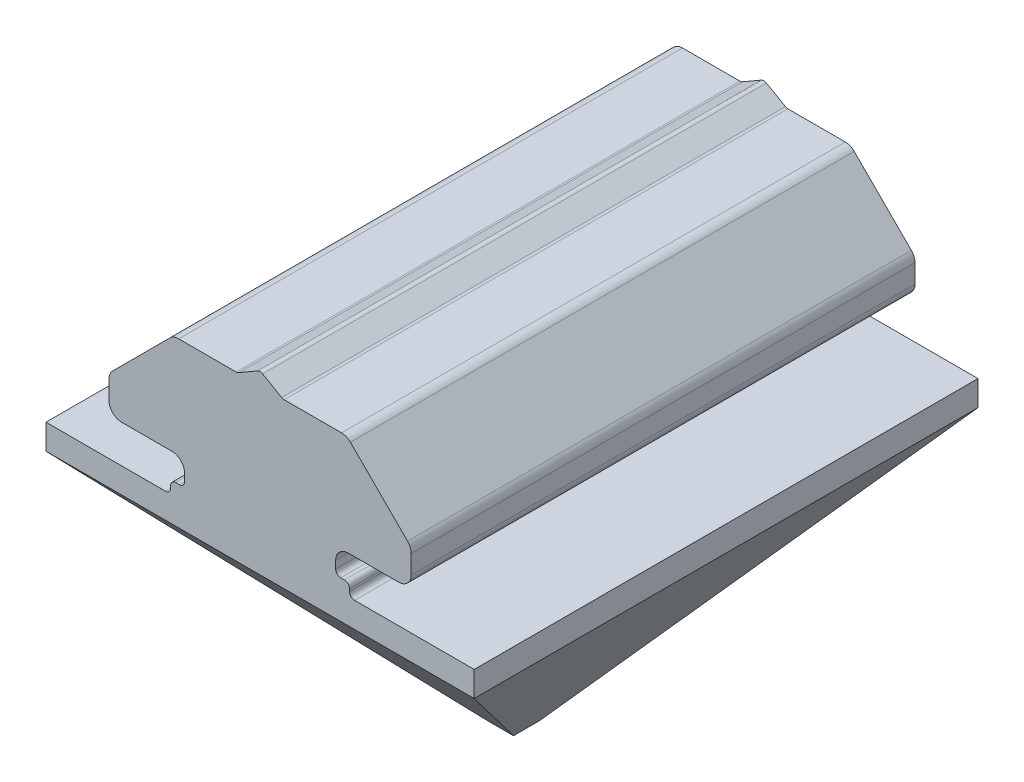
SolidWorks part; units mm, degrees
ref_plane "Front Plane" through (0, 0, 0) normal (0, 0, 1) x (1, 0, 0)
ref_plane "Top Plane" through (0, 0, 0) normal (0, 1, 0) x (1, 0, 0)
ref_plane "Right Plane" through (0, 0, 0) normal (1, 0, 0) x (0, 0, -1)
sketch "Sketch3" plane through (0, 0, 0) normal (0, 0, 1) x (1, 0, 0)
  line L44 (3.75, -10) -> (8.5, -10)
  line L45 (3.55, -9.7) -> (3.55, -9.8)
  line L46 (3.2, -9.5) -> (3.35, -9.5)
  line L47 (3, -9) -> (3, -9.3)
  line L48 (5.5, -8.5) -> (3.5, -8.5)
  line L49 (6, -7.2678) -> (6, -8)
  line L50 (3.5858, -4.6464) -> (5.8536, -6.9142)
  line L51 (0.9536, -4.5) -> (3.2322, -4.5)
  line L52 (0.1, -4.0381) -> (0.8536, -4.4732)
  line L53 (-0.8536, -4.4732) -> (-0.1, -4.0381)
  line L54 (-3.2322, -4.5) -> (-0.9536, -4.5)
  line L55 (-5.8536, -6.9142) -> (-3.5858, -4.6464)
  line L56 (-6, -8) -> (-6, -7.2678)
  line L57 (-3.5, -8.5) -> (-5.5, -8.5)
  line L58 (-3, -9.3) -> (-3, -9)
  line L59 (-3.35, -9.5) -> (-3.2, -9.5)
  line L60 (-3.55, -9.8) -> (-3.55, -9.7)
  line L61 (-8.5, -10) -> (-3.75, -10)
  line L62 (-8.5, -10) -> (-8.5, -11)
  line L63 (-8.5, -11) -> (8.5, -11)
  line L64 (8.5, -11) -> (8.5, -10)
  arc A44 (3.55, -9.8) -> (3.75, -10) centre (3.75, -9.8) ccw
  arc A45 (3.55, -9.7) -> (3.35, -9.5) centre (3.35, -9.7) ccw
  arc A46 (3, -9.3) -> (3.2, -9.5) centre (3.2, -9.3) ccw
  arc A47 (3.5, -8.5) -> (3, -9) centre (3.5, -9) ccw
  arc A48 (5.5, -8.5) -> (6, -8) centre (5.5, -8) ccw
  arc A49 (6, -7.2678) -> (5.8536, -6.9142) centre (5.5, -7.2678) ccw
  arc A50 (3.5858, -4.6464) -> (3.2322, -4.5) centre (3.2322, -5) ccw
  arc A51 (0.8536, -4.4732) -> (0.9536, -4.5) centre (0.9536, -4.3) ccw
  arc A52 (0.1, -4.0381) -> (-0.1, -4.0381) centre (0, -4.2113) ccw
  arc A53 (-0.9536, -4.5) -> (-0.8536, -4.4732) centre (-0.9536, -4.3) ccw
  arc A54 (-3.2322, -4.5) -> (-3.5858, -4.6464) centre (-3.2322, -5) ccw
  arc A55 (-5.8536, -6.9142) -> (-6, -7.2678) centre (-5.5, -7.2678) ccw
  arc A56 (-6, -8) -> (-5.5, -8.5) centre (-5.5, -8) ccw
  arc A57 (-3, -9) -> (-3.5, -8.5) centre (-3.5, -9) ccw
  arc A58 (-3.2, -9.5) -> (-3, -9.3) centre (-3.2, -9.3) ccw
  arc A59 (-3.35, -9.5) -> (-3.55, -9.7) centre (-3.35, -9.7) ccw
  arc A60 (-3.75, -10) -> (-3.55, -9.8) centre (-3.75, -9.8) ccw
extrude "Boss-Extrude1" add sketch "Sketch3" along normal blind 20
ref_plane "Düzlem1" through (0, -21, 0) normal (0, -1, 0) x (-1, 0, 0)
sketch "Çizim2" plane through (0, -21, 0) normal (0, -1, 0) x (-1, 0, 0)
  line L0 (8.5, -20) -> (-8.5, -20) construction
  line L1 (-0.5605, -9.5) -> (0.4395, -9.5)
  line L2 (-0.5605, -9.5) -> (-0.5605, -10.5)
  line L3 (-0.5605, -10.5) -> (0.4395, -10.5)
  line L4 (0.4395, -9.5) -> (0.4395, -10.5)
  line L5 (-0.5605, -9.5) -> (0.4395, -10.5) construction
  line L6 (-0.5605, -10.5) -> (0.4395, -9.5) construction
  point P0 (-0.0605, -10)
  dimension "D1" = 1
  dimension "D2" = 1
  dimension "D3" = 10
loft "Loft1" add profiles "Çizim2" section "Çizim2" section face at (0, -11, 10)
